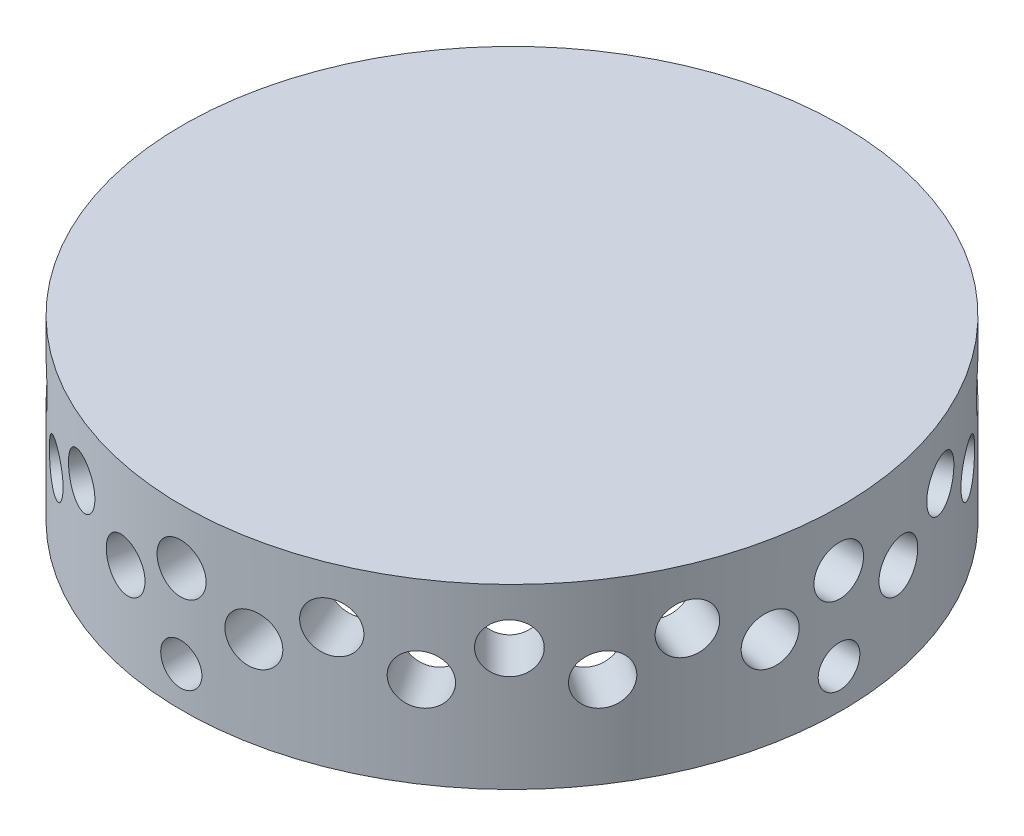
SolidWorks part; units mm, degrees
ref_plane "Płaszczyzna przednia" through (0, 0, 0) normal (0, 0, 1) x (1, 0, 0)
ref_plane "Płaszczyzna górna" through (0, 0, 0) normal (0, 1, 0) x (1, 0, 0)
ref_plane "Płaszczyzna prawa" through (0, 0, 0) normal (1, 0, 0) x (0, 0, -1)
sketch "Szkic1" plane through (0, 0, 0) normal (0, 0, 1) x (1, 0, 0)
  line L0 (0, -200.6294) -> (0, 200.6294) construction
  line L1 (0, 70.8485) -> (-83.5, 70.8485)
  line L2 (-83.5, 70.8485) -> (-83.5, 40.8485)
  line L4 (-83.5, 40.8485) -> (-83.5, 25.8485)
  line L5 (-83.5, 25.8485) -> (-70.5, 25.8485)
  line L6 (-70.5, 25.8485) -> (-70.5, 65.8485)
  line L7 (-70.5, 65.8485) -> (0, 65.8485)
  line L8 (0, 65.8485) -> (0, 70.8485)
  dimension "D1" = 70.5
  dimension "D2" = 40
  dimension "D3" = 5
  dimension "D5" = 13
revolve "Obrót1" add sketch "Szkic1" angle 360 about L0
ref_plane "Płaszczyzna1" through (83.5, 0, 0) normal (1, 0, 0) x (0, 0, -1)
sketch "Szkic2" plane through (83.5, 0, 0) normal (1, 0, 0) x (0, 0, -1)
  line L1 (83.5, 70.8485) -> (-83.5, 70.8485) construction
  circle A1 centre (-0.4671, 56.8485) radius 6.25
  dimension "D1" = 14
  dimension "D3" = 12.5
extrude "Wytnij-wyciągnięcie2" cut sketch "Szkic2" against normal up to next
sketch "Szkic4" plane through (83.5, 0, 0) normal (1, 0, 0) x (0, 0, -1)
  line L1 (-83.5, 25.8485) -> (83.5, 25.8485) construction
  circle A0 centre (-0.4671, 35.8485) radius 5.25
  dimension "D1" = 10.5
  dimension "D2" = 10
extrude "Wytnij-wyciągnięcie4" cut sketch "Szkic4" against normal blind 30
pattern_circular "Szyk kołowy2" count 4 over 360 of "Wytnij-wyciągnięcie4"
ref_plane "Płaszczyzna2" through (81.8956, 0, 16.29) normal (0.9808, 0, 0.1951) x (0, -1, 0)
sketch "Szkic8" plane through (81.8956, 0, 16.29) normal (0.9808, 0, 0.1951) x (0, -1, 0)
  line L0 (-70.8485, 83.5) -> (-70.8485, -83.5) construction
  circle A1 centre (-48.8485, 0) radius 6.25
  dimension "D1" = 22
  dimension "D2" = 12.5
extrude "Wytnij-wyciągnięcie5" cut sketch "Szkic8" against normal up to next
pattern_circular "Szyk kołowy3" count 16 over 360 of "Wytnij-wyciągnięcie2"
pattern_circular "Szyk kołowy4" count 16 over 360 of "Wytnij-wyciągnięcie5"
